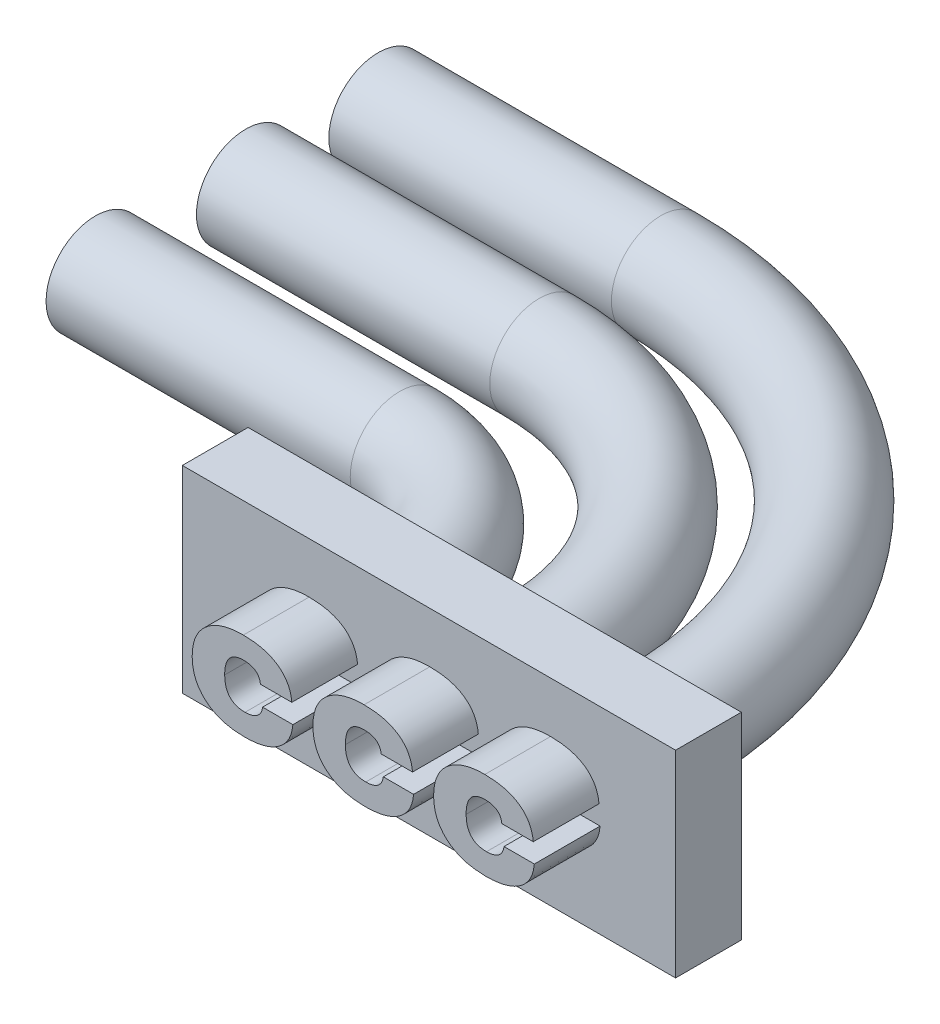
SolidWorks part; units mm, degrees
ref_plane "Front Plane" through (0, 0, 0) normal (0, 0, 1) x (1, 0, 0)
ref_plane "Top Plane" through (0, 0, 0) normal (0, 1, 0) x (1, 0, 0)
ref_plane "Right Plane" through (0, 0, 0) normal (1, 0, 0) x (0, 0, -1)
sketch "Sketch1" plane through (0, 0, 0) normal (0, 0, 1) x (1, 0, 0)
  line L1 (-7.5, 3) -> (7.5, 3)
  line L2 (-7.5, 3) -> (-7.5, -3)
  line L3 (-7.5, -3) -> (7.5, -3)
  line L4 (7.5, 3) -> (7.5, -3)
  line L5 (-7.5, 3) -> (7.5, -3) construction
  line L6 (-7.5, -3) -> (7.5, 3) construction
  point P0 (0, 0)
  dimension "D1" = 15
  dimension "D2" = 6
extrude "Boss-Extrude1" add sketch "Sketch1" along normal blind 2
sketch "Sketch2" plane through (0, 0, 2) normal (0, 0, 1) x (1, 0, 0)
  text T0 "CCC" font "Swis721 Blk BT" height in points 10
extrude "Boss-Extrude2" add sketch "Sketch2" along normal blind 2
sketch "Sketch3" plane through (0, 0, 0) normal (0, 1, 0) x (1, 0, 0)
  line L0 (7.5, 0) -> (-7.5, 0) construction
  line L1 (2.9487, 0) -> (4.4487, 0)
  line L2 (2.9487, 0) -> (2.9487, 12.6)
  line L3 (-3.644, -2) -> (-3.644, 5.3789) construction
  line L4 (4.4487, 0) -> (4.4487, 14.1)
  line L5 (-4.394, 0) -> (-2.894, 0)
  line L6 (-4.394, 0) -> (-4.394, 4)
  line L7 (0.0274, -2) -> (0.0274, 4.6797) construction
  line L8 (-2.894, 0) -> (-2.894, 4)
  line L9 (-2.894, 4) -> (-4.394, 4)
  line L10 (-0.7226, 0) -> (0.7774, 0)
  line L13 (-0.7226, 0) -> (-0.7226, 8.6)
  line L14 (3.6987, -2) -> (3.6987, 2.787) construction
  line L15 (0.7774, 0) -> (0.7774, 10.1)
  line L16 (0.7774, 10.1) -> (-2.4226, 10.1)
  line L17 (-2.4226, 14.1) -> (4.4487, 14.1)
  line L18 (-0.7226, 8.6) -> (-2.4226, 8.6)
  line L19 (-2.4226, 10.1) -> (-2.4226, 8.6)
  line L20 (-2.4226, 14.1) -> (-2.4226, 12.6)
  line L21 (-2.4226, 12.6) -> (2.9487, 12.6)
  dimension "D1" = 1.5
  dimension "D2" = 4
  dimension "D3" = 1.5
  dimension "D4" = 1.5
  dimension "D5" = 4.6
  dimension "D6" = 1.5
  dimension "D7" = 2.5
  dimension "D8" = 1.5
  dimension "D9" = 1.7
extrude "Boss-Extrude3" add sketch "Sketch3" along normal mid plane 4
sketch "Sketch4" [suppressed] plane through (0, 2, 0) normal (0, 1, 0) x (1, 0, 0)
  line L1 (-2.4226, 10.1) -> (-2.4226, 8.6) construction
  line L2 (-2.894, 4) -> (-11.894, 4)
  line L3 (-2.894, 4) -> (-2.894, 5.5)
  line L4 (-2.894, 5.5) -> (-11.894, 5.5)
  line L5 (-11.894, 4) -> (-11.894, 5.5)
  dimension "D1" = 9
extrude "Boss-Extrude4" [suppressed] add sketch "Sketch4" against normal up to surface (4 mm away)
sketch "Sketch5" [suppressed] plane through (-2.4226, 0, 0) normal (-1, 0, 0) x (0, 0, 1)
  line L4 (-10.1, -2) -> (-8.6, -2)
  line L5 (-8.6, -2) -> (-8.6, 2)
  line L6 (-8.6, 2) -> (-10.1, 2)
  line L7 (-10.1, 2) -> (-10.1, -2)
  line L8 (-10.1, -2) -> (-8.6, -2)
  line L9 (-8.6, -2) -> (-8.6, 2)
  line L10 (-8.6, 2) -> (-10.1, 2)
  line L11 (-10.1, 2) -> (-10.1, -2)
  line L12 (-14.1, -2) -> (-12.6, -2)
  line L13 (-12.6, -2) -> (-12.6, 2)
  line L14 (-12.6, 2) -> (-14.1, 2)
  line L15 (-14.1, 2) -> (-14.1, -2)
  line L16 (-14.1, -2) -> (-12.6, -2)
  line L17 (-12.6, -2) -> (-12.6, 2)
  line L18 (-12.6, 2) -> (-14.1, 2)
  line L19 (-14.1, 2) -> (-14.1, -2)
  dimension "D1" = 0
  dimension "D2" = 0
extrude "Boss-Extrude5" [suppressed] add sketch "Sketch5" along normal up to surface (9.4714 mm away)
sketch "Sketch6" plane through (0, 0, 0) normal (0, 0, -1) x (-1, 0, 0)
  line L0 (-4.4487, 0) -> (-2.9487, 0) construction
  line L1 (-4.4487, 2) -> (-4.4487, -2) construction
  line L2 (-2.9487, 2) -> (-2.9487, -2) construction
  line L3 (-0.7774, 0) -> (0.7226, 0) construction
  line L4 (-0.7774, 2) -> (-0.7774, -2) construction
  line L5 (0.7226, 2) -> (0.7226, -2) construction
  line L6 (2.894, 0) -> (4.394, 0) construction
  line L7 (2.894, 2) -> (2.894, -2) construction
  line L8 (4.394, 2) -> (4.394, -2) construction
  circle A0 centre (-3.6987, 0) radius 1.5
  dimension "D1" = 3
sketch "Sketch7" plane through (0, 0, 0) normal (0, 0, -1) x (-1, 0, 0)
  circle A0 centre (0, 0) radius 1.5
  dimension "D1" = 3
sketch "Sketch8" plane through (0, 0, 0) normal (0, 0, -1) x (-1, 0, 0)
  line L0 (2.894, 0) -> (4.394, 0) construction
  circle A0 centre (3.644, 0) radius 1.5
  dimension "D1" = 3
sketch "Sketch9" plane through (0, 0, 0) normal (0, 1, 0) x (1, 0, 0)
  line L0 (-3.644, 0) -> (-3.644, 0.75)
  line L1 (-2.894, 0) -> (-4.394, 0) construction
  line L2 (-7.644, 4.75) -> (-16.894, 4.75)
  arc A0 (-3.644, 0.75) -> (-7.644, 4.75) centre (-7.644, 0.75) ccw
  point P7 (-3.644, 4.75)
  dimension "D3" = 4
  dimension "D1" = 4.75
  dimension "D2" = 13.25
sketch "Sketch10" plane through (0, 0, 0) normal (0, 1, 0) x (1, 0, 0)
  line L0 (0.0274, 0) -> (0.0274, 1.35)
  line L1 (0.7774, 0) -> (-0.7226, 0) construction
  line L2 (-7.9726, 9.35) -> (-16.894, 9.35)
  arc A0 (0.0274, 1.35) -> (-7.9726, 9.35) centre (-7.9726, 1.35) ccw
  point P7 (0.0274, 9.35)
  dimension "D3" = 8
  dimension "D1" = 16.9214
  dimension "D2" = 9.35
sketch "Sketch11" plane through (0, 0, 0) normal (0, 1, 0) x (1, 0, 0)
  line L0 (3.6987, 0) -> (3.6987, 1.35)
  line L1 (4.4487, 0) -> (2.9487, 0) construction
  line L2 (-8.3013, 13.35) -> (-16.894, 13.35)
  arc A0 (3.6987, 1.35) -> (-8.3013, 13.35) centre (-8.3013, 1.35) ccw
  point P7 (3.6987, 13.35)
  dimension "D3" = 12
  dimension "D1" = 13.35
  dimension "D2" = 20.5928
sketch "Sketch12" plane through (7.5, 0, 0) normal (1, 0, 0) x (0, 0, -1)
  line L1 (0, -3) -> (14.1, -3)
  line L2 (0, -3) -> (0, 2)
  line L3 (0, 2) -> (14.1, 2)
  line L4 (14.1, -3) -> (14.1, 2)
extrude "Cut-Extrude1" cut sketch "Sketch12" against normal through all
sweep "Sweep1" add profiles "Sketch8" path "Sketch9"
sweep "Sweep2" add profiles "Sketch7" path "Sketch10"
sweep "Sweep3" add profiles "Sketch6" path "Sketch11"
